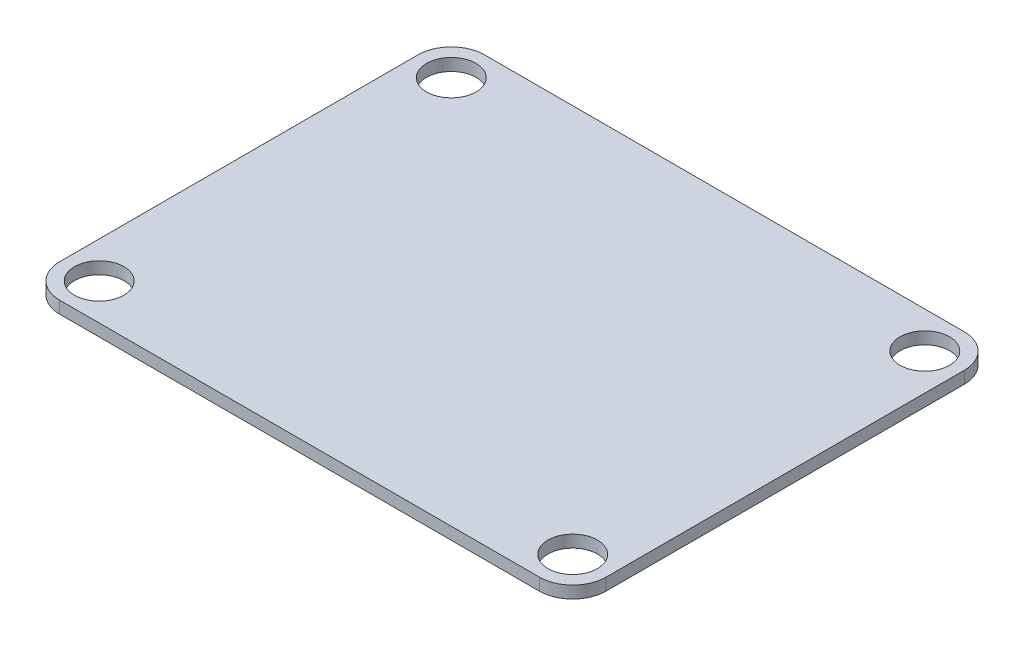
SolidWorks part; units mm, degrees
ref_plane "Front Plane" through (0, 0, 0) normal (0, 0, 1) x (1, 0, 0)
ref_plane "Top Plane" through (0, 0, 0) normal (0, 1, 0) x (1, 0, 0)
ref_plane "Right Plane" through (0, 0, 0) normal (1, 0, 0) x (0, 0, -1)
sketch "Sketch1" plane through (0, 0, 0) normal (0, 1, 0) x (1, 0, 0)
  line L1 (-114.3, 88.9) -> (114.3, 88.9)
  line L2 (-114.3, 88.9) -> (-114.3, -88.9)
  line L3 (-114.3, -88.9) -> (114.3, -88.9)
  line L4 (114.3, 88.9) -> (114.3, -88.9)
  line L5 (-114.3, 88.9) -> (114.3, -88.9) construction
  line L6 (-114.3, -88.9) -> (114.3, 88.9) construction
  point P0 (0, 0)
  dimension "D1" = 177.8
  dimension "10" = 228.6
extrude "Boss-Extrude1" add sketch "Sketch1" along normal blind 5.08
sketch "Sketch2" plane through (0, 5.08, 0) normal (0, 1, 0) x (1, 0, 0)
  line L0 (-99.06, 73.66) -> (-99.06, 88.9) construction
  line L1 (114.3, 88.9) -> (-114.3, 88.9) construction
  line L2 (-99.06, 73.66) -> (-114.3, 73.66) construction
  line L3 (-114.3, 88.9) -> (-114.3, -88.9) construction
  line L4 (-99.06, -73.66) -> (-114.3, -73.66) construction
  line L5 (-99.06, -73.66) -> (-99.06, -88.9) construction
  line L6 (-114.3, -88.9) -> (114.3, -88.9) construction
  line L7 (99.06, 73.66) -> (99.06, 88.9) construction
  line L8 (99.06, 73.66) -> (114.3, 73.66) construction
  line L9 (114.3, -88.9) -> (114.3, 88.9) construction
  line L10 (99.06, -73.66) -> (99.06, -88.9) construction
  line L11 (99.06, -73.66) -> (114.3, -73.66) construction
  circle A0 centre (-99.06, 73.66) radius 10.3505
  circle A1 centre (99.06, 73.66) radius 10.3505
  circle A2 centre (99.06, -73.66) radius 10.3505
  circle A3 centre (-99.06, -73.66) radius 10.3505
  dimension "D1" = 20.701
  dimension "D2" = 15.24
extrude "Cut-Extrude1" cut sketch "Sketch2" against normal through all
fillet "Fillet3" radius 13.97 4 edges at (114.3, 2.54, -88.9) (114.3, 2.54, 88.9) (-114.3, 2.54, -88.9) (-114.3, 2.54, 88.9)
sketch "Sketch3" plane through (0, 5.08, 0) normal (0, 1, 0) x (1, 0, 0)
  line L0 (-114.3, 0) -> (114.3, 0) construction
  line L1 (-114.3, 74.93) -> (-114.3, -74.93) construction
  line L2 (114.3, -74.93) -> (114.3, 74.93) construction
  line L3 (0, 88.9) -> (0, -88.9) construction
  line L4 (100.33, 88.9) -> (-100.33, 88.9) construction
  line L5 (-100.33, -88.9) -> (100.33, -88.9) construction
  point P12 (0, 0)
